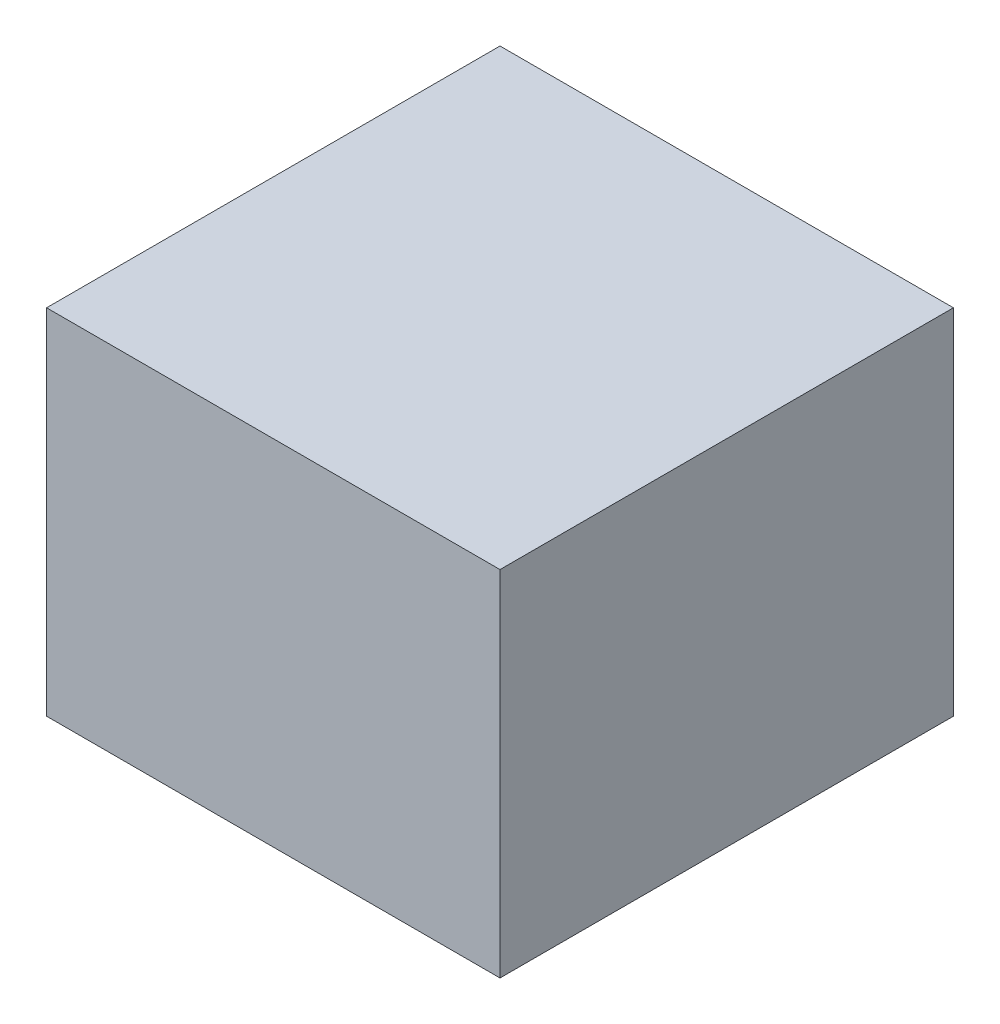
SolidWorks part; units mm, degrees
ref_plane "Front Plane" through (0, 0, 0) normal (0, 0, 1) x (1, 0, 0)
ref_plane "Top Plane" through (0, 0, 0) normal (0, 1, 0) x (1, 0, 0)
ref_plane "Right Plane" through (0, 0, 0) normal (1, 0, 0) x (0, 0, -1)
sketch "Sketch1" plane through (0, 0, 0) normal (0, 1, 0) x (1, 0, 0)
  line L1 (0, 0) -> (42.3, 0)
  line L2 (0, 0) -> (0, 42.3)
  line L3 (0, 42.3) -> (42.3, 42.3)
  line L4 (42.3, 0) -> (42.3, 42.3)
  dimension "D1" = 42.3
  dimension "D2" = 42.3
extrude "Boss-Extrude1" add sketch "Sketch1" along normal blind 33 contours L2 L1 L4 L3
sketch "Sketch2" plane through (0, 0, 0) normal (0, -1, 0) x (-1, 0, 0)
  line L0 (0, 42.3) -> (-42.3, 0)
  line L1 (-0.572, 0) -> (-42.3, 42.3)
  circle A0 centre (-21.15, 21.15) radius 2.5
  dimension "D1" = 5
extrude "Boss-Extrude3" add sketch "Sketch2" along normal blind 18 contours A0
sketch "Sketch5" plane through (0, 0, 0) normal (0, 1, 0) x (1, 0, 0)
  line L1 (36.65, 36.65) -> (5.65, 36.65)
  line L2 (36.65, 36.65) -> (36.65, 5.65)
  line L3 (36.65, 5.65) -> (5.65, 5.65)
  line L4 (5.65, 36.65) -> (5.65, 5.65)
  line L5 (36.65, 36.65) -> (5.65, 5.65) construction
  line L6 (36.65, 5.65) -> (5.65, 36.65) construction
  circle A0 centre (21.15, 21.15) radius 11
  point P0 (21.15, 21.15)
  dimension "D3" = 11
  dimension "D1" = 31
  dimension "D2" = 31
hole_wizard "Hole for M3 300® SC Nuts (SP)2" positions "Sketch8" profile "Sketch9" hole size "M3x0.5" standard "PEM® Metric"
sketch "Sketch8" plane through (0, 0, 0) normal (0, -1, 0) x (-1, 0, 0)
  point P0 (-5.65, 36.65)
  point P3 (-5.65, 5.65)
  point P6 (-36.65, 5.65)
  point P9 (-36.65, 36.65)
sketch "Sketch9" plane through (5.65, 0, -36.65) normal (1, 0, 0) x (0, 0, -1)
  line L0 (0, 0) -> (0, 5.7678)
  line L1 (0, 5.7678) -> (2.11, 4.5)
  line L2 (2.11, 4.5) -> (2.11, 0)
  line L5 (2.11, 0) -> (0, 0)
  line L10 (0, 5.7678) -> (-2.11, 4.5) construction
  line L11 (0, -6.35) -> (0, 107.95) construction
  dimension "Hole Dia." = 4.22
  dimension "Hole Depth" = 4.5
  dimension "Drill Angle" = 118
extrude "Boss-Extrude4" add sketch "Sketch5" against normal blind 2 contours A0
